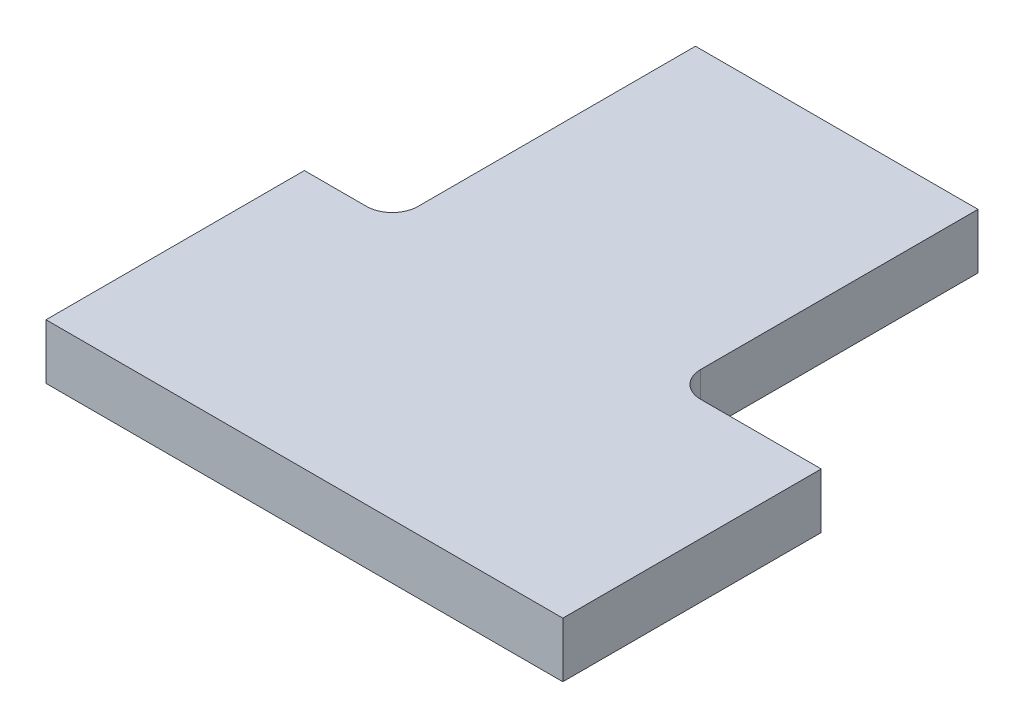
SolidWorks part; units mm, degrees
ref_plane "Ebene vorne" through (0, 0, 0) normal (0, 0, 1) x (1, 0, 0)
ref_plane "Ebene oben" through (0, 0, 0) normal (0, 1, 0) x (1, 0, 0)
ref_plane "Ebene rechts" through (0, 0, 0) normal (1, 0, 0) x (0, 0, -1)
sketch "Skizze1" plane through (0, 0, 0) normal (0, 1, 0) x (1, 0, 0)
  line L0 (4, 3.75) -> (4.85, 3.75)
  line L1 (-7.5, 3.75) -> (-5.7, 3.75)
  line L2 (-7.5, 3.75) -> (-7.5, -3.75)
  line L3 (-7.5, -3.75) -> (7.5, -3.75)
  line L4 (7.5, 3.75) -> (7.5, -3.75)
  line L5 (-7.5, 3.75) -> (7.5, -3.75) construction
  line L6 (-7.5, -3.75) -> (7.5, 3.75) construction
  line L7 (3.25, 12.55) -> (-4.95, 12.55)
  line L8 (-4.95, 12.55) -> (-4.95, 4.5)
  line L9 (3.25, 12.55) -> (3.25, 4.5)
  line L10 (4.85, 3.75) -> (7.5, 3.75)
  arc A0 (3.25, 4.5) -> (4, 3.75) centre (4, 4.5) ccw
  arc A1 (-4.95, 4.5) -> (-5.7, 3.75) centre (-5.7, 4.5) cw
  point P0 (0, 0)
  point P14 (3.25, 3.75)
  point P17 (-4.95, 3.75)
  dimension "D1" = 0.75
extrude "Aufsatz-Linear austragen1" add sketch "Skizze1" along normal blind 1.6
